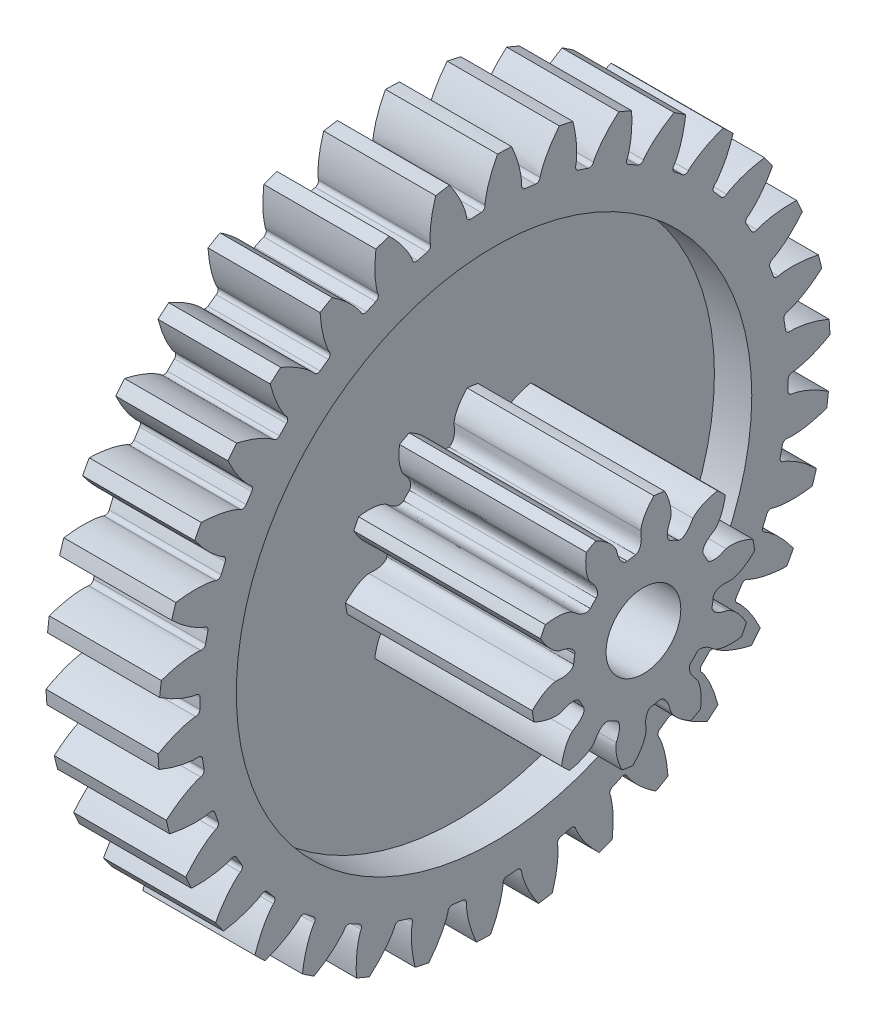
SolidWorks part; units mm, degrees
ref_plane "Plan de face" through (0, 0, 0) normal (0, 0, 1) x (1, 0, 0)
ref_plane "Plan de dessus" through (0, 0, 0) normal (0, 1, 0) x (1, 0, 0)
ref_plane "Plan de droite" through (0, 0, 0) normal (1, 0, 0) x (0, 0, -1)
sketch "Esquisse2" plane through (0, 0, 0) normal (1, 0, 0) x (0, 0, -1)
  arc A0 (8.9927, 0.363) -> (8.9699, 0.736) centre (0, 0) ccw
  arc A1 (8.7729, 2.0092) -> (8.6819, 2.3717) centre (0, 0) ccw
  arc A2 (8.2543, 3.587) -> (8.0983, 3.9266) centre (0, 0) ccw
  arc A3 (7.4547, 5.0426) -> (7.2389, 5.3478) centre (0, 0) ccw
  arc A4 (6.4012, 6.3266) -> (6.133, 6.5869) centre (0, 0) ccw
  arc A5 (5.1297, 7.395) -> (4.8182, 7.6016) centre (0, 0) ccw
  arc A6 (3.6835, 8.2117) -> (3.3394, 8.3575) centre (0, 0) ccw
  arc A7 (2.1119, 8.7487) -> (1.7468, 8.8289) centre (0, 0) ccw
  arc A8 (0.4683, 8.9878) -> (0.0948, 8.9995) centre (0, 0) ccw
  arc A9 (-1.1911, 8.9208) -> (-1.5605, 8.8637) centre (0, 0) ccw
  arc A10 (-2.8101, 8.5501) -> (-3.1626, 8.426) centre (0, 0) ccw
  arc A11 (-4.3333, 7.8881) -> (-4.657, 7.7014) centre (0, 0) ccw
  arc A12 (-5.7089, 6.9576) -> (-5.9929, 6.7146) centre (0, 0) ccw
  arc A13 (-6.8902, 5.7901) -> (-7.1246, 5.499) centre (0, 0) ccw
  arc A14 (-7.8368, 4.4254) -> (-8.0138, 4.0963) centre (0, 0) ccw
  arc A15 (-8.5165, 2.9101) -> (-8.63, 2.554) centre (0, 0) ccw
  arc A16 (-8.9063, 1.2956) -> (-8.9524, 0.9247) centre (0, 0) ccw
  arc A17 (-8.9927, -0.363) -> (-8.9699, -0.736) centre (0, 0) ccw
  arc A18 (-8.7729, -2.0092) -> (-8.6819, -2.3717) centre (0, 0) ccw
  arc A19 (-8.2543, -3.587) -> (-8.0983, -3.9266) centre (0, 0) ccw
  arc A20 (-7.4547, -5.0426) -> (-7.2389, -5.3478) centre (0, 0) ccw
  arc A21 (-6.4012, -6.3266) -> (-6.133, -6.5869) centre (0, 0) ccw
  arc A22 (-5.1297, -7.395) -> (-4.8182, -7.6016) centre (0, 0) ccw
  arc A23 (-3.6835, -8.2117) -> (-3.3394, -8.3575) centre (0, 0) ccw
  arc A24 (-2.1119, -8.7487) -> (-1.7468, -8.8289) centre (0, 0) ccw
  arc A25 (-0.4683, -8.9878) -> (-0.0948, -8.9995) centre (0, 0) ccw
  arc A26 (1.1911, -8.9208) -> (1.5605, -8.8637) centre (0, 0) ccw
  arc A27 (2.8101, -8.5501) -> (3.1626, -8.426) centre (0, 0) ccw
  arc A28 (4.3333, -7.8881) -> (4.657, -7.7014) centre (0, 0) ccw
  arc A29 (5.7089, -6.9576) -> (5.9929, -6.7146) centre (0, 0) ccw
  arc A30 (6.8902, -5.7901) -> (7.1246, -5.499) centre (0, 0) ccw
  arc A31 (7.8368, -4.4254) -> (8.0138, -4.0963) centre (0, 0) ccw
  arc A32 (8.5165, -2.9101) -> (8.63, -2.554) centre (0, 0) ccw
  arc A33 (8.9063, -1.2956) -> (8.9524, -0.9247) centre (0, 0) ccw
  arc A34 (7.987, 0) -> (7.8742, -0.1109) centre (7.9867, -0.1125) ccw
  arc A35 (7.8657, -0.3818) -> (7.9719, -0.4996) centre (7.9781, -0.3873) ccw
  arc A36 (7.8657, -0.3818) -> (7.8742, -0.1109) centre (0, 0) ccw
  arc A37 (7.851, 1.4676) -> (7.7605, 1.3379) centre (7.8714, 1.357) ccw
  arc A38 (7.802, 1.07) -> (7.928, 0.9737) centre (7.9134, 1.0853) ccw
  arc A39 (7.802, 1.07) -> (7.7605, 1.3379) centre (0, 0) ccw
  arc A40 (7.4477, 2.8852) -> (7.3826, 2.7411) centre (7.488, 2.7802) ccw
  arc A41 (7.4725, 2.4854) -> (7.6141, 2.4139) centre (7.5793, 2.5209) ccw
  arc A42 (7.4725, 2.4854) -> (7.3826, 2.7411) centre (0, 0) ccw
  arc A43 (6.7907, 4.2046) -> (6.7532, 4.0509) centre (6.8497, 4.1088) ccw
  arc A44 (6.8886, 3.8161) -> (7.0409, 3.7719) centre (6.987, 3.8706) ccw
  arc A45 (6.8886, 3.8161) -> (6.7532, 4.0509) centre (0, 0) ccw
  arc A46 (5.9025, 5.3808) -> (5.8938, 5.2229) centre (5.978, 5.2975) ccw
  arc A47 (6.0701, 5.0169) -> (6.2279, 5.0014) centre (6.1568, 5.0886) ccw
  arc A48 (6.0701, 5.0169) -> (5.8938, 5.2229) centre (0, 0) ccw
  arc A49 (4.8132, 6.3738) -> (4.8338, 6.2169) centre (4.9028, 6.3057) ccw
  arc A50 (5.0449, 6.0469) -> (5.2029, 6.0607) centre (5.117, 6.1333) ccw
  arc A51 (5.0449, 6.0469) -> (4.8338, 6.2169) centre (0, 0) ccw
  arc A52 (3.5601, 7.1497) -> (3.6091, 6.9993) centre (3.6607, 7.0993) ccw
  arc A53 (3.8479, 6.8709) -> (4.0007, 6.9135) centre (3.9028, 6.9691) ccw
  arc A54 (3.8479, 6.8709) -> (3.6091, 6.9993) centre (0, 0) ccw
  arc A55 (2.1857, 7.6821) -> (2.2616, 7.5433) centre (2.2939, 7.651) ccw
  arc A56 (2.5198, 7.461) -> (2.6622, 7.5309) centre (2.5558, 7.5676) ccw
  arc A57 (2.5198, 7.461) -> (2.2616, 7.5433) centre (0, 0) ccw
  arc A58 (0.7369, 7.9529) -> (0.837, 7.8304) centre (0.8489, 7.9423) ccw
  arc A59 (1.106, 7.797) -> (1.2331, 7.8918) centre (1.1218, 7.9083) ccw
  arc A60 (1.106, 7.797) -> (0.837, 7.8304) centre (0, 0) ccw
  arc A61 (-0.7369, 7.9529) -> (-0.6161, 7.8509) centre (-0.6249, 7.963) ccw
  arc A62 (-0.3455, 7.8674) -> (-0.2381, 7.984) centre (-0.3505, 7.9798) ccw
  arc A63 (-0.3455, 7.8674) -> (-0.6161, 7.8509) centre (0, 0) ccw
  arc A64 (-2.1857, 7.6821) -> (-2.0482, 7.604) centre (-2.0775, 7.7126) ccw
  arc A65 (-1.7853, 7.67) -> (-1.7011, 7.8044) centre (-1.8108, 7.7795) ccw
  arc A66 (-1.7853, 7.67) -> (-2.0482, 7.604) centre (0, 0) ccw
  arc A67 (-3.5601, 7.1497) -> (-3.4106, 7.0981) centre (-3.4593, 7.1996) ccw
  arc A68 (-3.1642, 7.2113) -> (-3.1062, 7.3589) centre (-3.2095, 7.3143) ccw
  arc A69 (-3.1642, 7.2113) -> (-3.4106, 7.0981) centre (0, 0) ccw
  arc A70 (-4.8132, 6.3738) -> (-4.6568, 6.3506) centre (-4.7233, 6.4413) ccw
  arc A71 (-4.4354, 6.5071) -> (-4.4055, 6.6628) centre (-4.4988, 6.6001) ccw
  arc A72 (-4.4354, 6.5071) -> (-4.6568, 6.3506) centre (0, 0) ccw
  arc A73 (-5.9025, 5.3808) -> (-5.7444, 5.3868) centre (-5.8265, 5.4637) ccw
  arc A74 (-5.5556, 5.5813) -> (-5.5547, 5.7399) centre (-5.635, 5.661) ccw
  arc A75 (-5.5556, 5.5813) -> (-5.7444, 5.3868) centre (0, 0) ccw
  arc A76 (-6.7907, 4.2046) -> (-6.6364, 4.2395) centre (-6.7312, 4.3001) ccw
  arc A77 (-6.4866, 4.4654) -> (-6.5149, 4.6215) centre (-6.5792, 4.5292) ccw
  arc A78 (-6.4866, 4.4654) -> (-6.6364, 4.2395) centre (0, 0) ccw
  arc A79 (-7.4477, 2.8852) -> (-7.3024, 2.9479) centre (-7.4067, 2.99) ccw
  arc A80 (-7.1966, 3.1975) -> (-7.2531, 3.3457) centre (-7.2995, 3.2432) ccw
  arc A81 (-7.1966, 3.1975) -> (-7.3024, 2.9479) centre (0, 0) ccw
  arc A82 (-7.851, 1.4676) -> (-7.7198, 1.5559) centre (-7.83, 1.5781) ccw
  arc A83 (-7.6616, 1.8207) -> (-7.7444, 1.956) centre (-7.7711, 1.8467) ccw
  arc A84 (-7.6616, 1.8207) -> (-7.7198, 1.5559) centre (0, 0) ccw
  arc A85 (-7.987, 0) -> (-7.8742, 0.1109) centre (-7.9867, 0.1125) ccw
  arc A86 (-7.8657, 0.3818) -> (-7.9719, 0.4996) centre (-7.9781, 0.3873) ccw
  arc A87 (-7.8657, 0.3818) -> (-7.8742, 0.1109) centre (0, 0) ccw
  arc A88 (-7.851, -1.4676) -> (-7.7605, -1.3379) centre (-7.8714, -1.357) ccw
  arc A89 (-7.802, -1.07) -> (-7.928, -0.9737) centre (-7.9134, -1.0853) ccw
  arc A90 (-7.802, -1.07) -> (-7.7605, -1.3379) centre (0, 0) ccw
  arc A91 (-7.4477, -2.8852) -> (-7.3826, -2.7411) centre (-7.488, -2.7802) ccw
  arc A92 (-7.4725, -2.4854) -> (-7.6141, -2.4139) centre (-7.5793, -2.5209) ccw
  arc A93 (-7.4725, -2.4854) -> (-7.3826, -2.7411) centre (0, 0) ccw
  arc A94 (-6.7907, -4.2046) -> (-6.7532, -4.0509) centre (-6.8497, -4.1088) ccw
  arc A95 (-6.8886, -3.8161) -> (-7.0409, -3.7719) centre (-6.987, -3.8706) ccw
  arc A96 (-6.8886, -3.8161) -> (-6.7532, -4.0509) centre (0, 0) ccw
  arc A97 (-5.9025, -5.3808) -> (-5.8938, -5.2229) centre (-5.978, -5.2975) ccw
  arc A98 (-6.0701, -5.0169) -> (-6.2279, -5.0014) centre (-6.1568, -5.0886) ccw
  arc A99 (-6.0701, -5.0169) -> (-5.8938, -5.2229) centre (0, 0) ccw
  arc A100 (-4.8132, -6.3738) -> (-4.8338, -6.2169) centre (-4.9028, -6.3057) ccw
  arc A101 (-5.0449, -6.0469) -> (-5.2029, -6.0607) centre (-5.117, -6.1333) ccw
  arc A102 (-5.0449, -6.0469) -> (-4.8338, -6.2169) centre (0, 0) ccw
  arc A103 (-3.5601, -7.1497) -> (-3.6091, -6.9993) centre (-3.6607, -7.0993) ccw
  arc A104 (-3.8479, -6.8709) -> (-4.0007, -6.9135) centre (-3.9028, -6.9691) ccw
  arc A105 (-3.8479, -6.8709) -> (-3.6091, -6.9993) centre (0, 0) ccw
  arc A106 (-2.1857, -7.6821) -> (-2.2616, -7.5433) centre (-2.2939, -7.651) ccw
  arc A107 (-2.5198, -7.461) -> (-2.6622, -7.5309) centre (-2.5558, -7.5676) ccw
  arc A108 (-2.5198, -7.461) -> (-2.2616, -7.5433) centre (0, 0) ccw
  arc A109 (-0.7369, -7.9529) -> (-0.837, -7.8304) centre (-0.8489, -7.9423) ccw
  arc A110 (-1.106, -7.797) -> (-1.2331, -7.8918) centre (-1.1218, -7.9083) ccw
  arc A111 (-1.106, -7.797) -> (-0.837, -7.8304) centre (0, 0) ccw
  arc A112 (0.7369, -7.9529) -> (0.6161, -7.8509) centre (0.6249, -7.963) ccw
  arc A113 (0.3455, -7.8674) -> (0.2381, -7.984) centre (0.3505, -7.9798) ccw
  arc A114 (0.3455, -7.8674) -> (0.6161, -7.8509) centre (0, 0) ccw
  arc A115 (2.1857, -7.6821) -> (2.0482, -7.604) centre (2.0775, -7.7126) ccw
  arc A116 (1.7853, -7.67) -> (1.7011, -7.8044) centre (1.8108, -7.7795) ccw
  arc A117 (1.7853, -7.67) -> (2.0482, -7.604) centre (0, 0) ccw
  arc A118 (3.5601, -7.1497) -> (3.4106, -7.0981) centre (3.4593, -7.1996) ccw
  arc A119 (3.1642, -7.2113) -> (3.1062, -7.3589) centre (3.2095, -7.3143) ccw
  arc A120 (3.1642, -7.2113) -> (3.4106, -7.0981) centre (0, 0) ccw
  arc A121 (4.8132, -6.3738) -> (4.6568, -6.3506) centre (4.7233, -6.4413) ccw
  arc A122 (4.4354, -6.5071) -> (4.4055, -6.6628) centre (4.4988, -6.6001) ccw
  arc A123 (4.4354, -6.5071) -> (4.6568, -6.3506) centre (0, 0) ccw
  arc A124 (5.9025, -5.3808) -> (5.7444, -5.3868) centre (5.8265, -5.4637) ccw
  arc A125 (5.5556, -5.5813) -> (5.5547, -5.7399) centre (5.635, -5.661) ccw
  arc A126 (5.5556, -5.5813) -> (5.7444, -5.3868) centre (0, 0) ccw
  arc A127 (6.7907, -4.2046) -> (6.6364, -4.2395) centre (6.7312, -4.3001) ccw
  arc A128 (6.4866, -4.4654) -> (6.5149, -4.6215) centre (6.5792, -4.5292) ccw
  arc A129 (6.4866, -4.4654) -> (6.6364, -4.2395) centre (0, 0) ccw
  arc A130 (7.4477, -2.8852) -> (7.3024, -2.9479) centre (7.4067, -2.99) ccw
  arc A131 (7.1966, -3.1975) -> (7.2531, -3.3457) centre (7.2995, -3.2432) ccw
  arc A132 (7.1966, -3.1975) -> (7.3024, -2.9479) centre (0, 0) ccw
  arc A133 (7.851, -1.4676) -> (7.7198, -1.5559) centre (7.83, -1.5781) ccw
  arc A134 (7.6616, -1.8207) -> (7.7444, -1.956) centre (7.7711, -1.8467) ccw
  arc A135 (7.6616, -1.8207) -> (7.7198, -1.5559) centre (0, 0) ccw
  circle A136 centre (0, 0) radius 1
  spline S0 degree 3 poles (7.987, 0) (8.0286, 0) (8.2037, 0.0282) (8.4818, 0.1115) (8.7713, 0.2415) (8.9323, 0.3284) (8.9927, 0.363) knots 0 0 0 0 0.124841 0.528779 0.867842 1.076016 1.076016 1.076016 1.076016
  spline S1 degree 3 poles (7.928, 0.9737) (7.9687, 0.9787) (8.146, 0.9721) (8.4321, 0.9233) (8.7354, 0.8295) (8.9058, 0.7629) (8.9699, 0.736) knots 0 0 0 0 0.124841 0.528779 0.867842 1.076016 1.076016 1.076016 1.076016
  spline S2 degree 3 poles (7.851, 1.4676) (7.8919, 1.4753) (8.0589, 1.5352) (8.3169, 1.6682) (8.5776, 1.8491) (8.7199, 1.9642) (8.7729, 2.0092) knots 0 0 0 0 0.124841 0.528779 0.867842 1.076016 1.076016 1.076016 1.076016
  spline S3 degree 3 poles (7.6141, 2.4139) (7.6532, 2.4263) (7.8287, 2.4523) (8.1189, 2.4569) (8.4342, 2.4205) (8.6139, 2.3863) (8.6819, 2.3717) knots 0 0 0 0 0.124841 0.528779 0.867842 1.076016 1.076016 1.076016 1.076016
  spline S4 degree 3 poles (7.4477, 2.8852) (7.4865, 2.9003) (7.6396, 2.9898) (7.8687, 3.168) (8.0918, 3.3938) (8.2105, 3.533) (8.2543, 3.587) knots 0 0 0 0 0.124841 0.528779 0.867842 1.076016 1.076016 1.076016 1.076016
  spline S5 degree 3 poles (7.0409, 3.7719) (7.0771, 3.7913) (7.2448, 3.8491) (7.5292, 3.9069) (7.8458, 3.9291) (8.0288, 3.9285) (8.0983, 3.9266) knots 0 0 0 0 0.124841 0.528779 0.867842 1.076016 1.076016 1.076016 1.076016
  spline S6 degree 3 poles (6.7907, 4.2046) (6.8261, 4.2265) (6.9601, 4.3427) (7.1526, 4.5599) (7.3304, 4.8229) (7.4215, 4.9815) (7.4547, 5.0426) knots 0 0 0 0 0.124841 0.528779 0.867842 1.076016 1.076016 1.076016 1.076016
  spline S7 degree 3 poles (6.2279, 5.0014) (6.2599, 5.0271) (6.4141, 5.1148) (6.6831, 5.2239) (6.9903, 5.3039) (7.1702, 5.3369) (7.2389, 5.3478) knots 0 0 0 0 0.124841 0.528779 0.867842 1.076016 1.076016 1.076016 1.076016
  spline S8 degree 3 poles (5.9025, 5.3808) (5.9332, 5.4088) (6.0436, 5.5477) (6.193, 5.7966) (6.3194, 6.0877) (6.3798, 6.2604) (6.4012, 6.3266) knots 0 0 0 0 0.124841 0.528779 0.867842 1.076016 1.076016 1.076016 1.076016
  spline S9 degree 3 poles (5.2029, 6.0607) (5.2296, 6.0918) (5.3651, 6.2063) (5.6094, 6.363) (5.8967, 6.498) (6.0675, 6.5636) (6.133, 6.5869) knots 0 0 0 0 0.124841 0.528779 0.867842 1.076016 1.076016 1.076016 1.076016
  spline S10 degree 3 poles (4.8132, 6.3738) (4.8383, 6.407) (4.9213, 6.5637) (5.0224, 6.8358) (5.0932, 7.1452) (5.1208, 7.3261) (5.1297, 7.395) knots 0 0 0 0 0.124841 0.528779 0.867842 1.076016 1.076016 1.076016 1.076016
  spline S11 degree 3 poles (4.0007, 6.9135) (4.0212, 6.949) (4.1333, 7.0864) (4.3447, 7.2854) (4.6022, 7.4709) (4.7581, 7.5667) (4.8182, 7.6016) knots 0 0 0 0 0.124841 0.528779 0.867842 1.076016 1.076016 1.076016 1.076016
  spline S12 degree 3 poles (3.5601, 7.1497) (3.5787, 7.1869) (3.6315, 7.3563) (3.6808, 7.6423) (3.6935, 7.9594) (3.6875, 8.1423) (3.6835, 8.2117) knots 0 0 0 0 0.124841 0.528779 0.867842 1.076016 1.076016 1.076016 1.076016
  spline S13 degree 3 poles (2.6622, 7.5309) (2.6759, 7.5696) (2.7608, 7.7253) (2.932, 7.9596) (3.1511, 8.1893) (3.2867, 8.3122) (3.3394, 8.3575) knots 0 0 0 0 0.124841 0.528779 0.867842 1.076016 1.076016 1.076016 1.076016
  spline S14 degree 3 poles (2.1857, 7.6821) (2.1971, 7.7221) (2.2179, 7.8983) (2.2139, 8.1885) (2.1681, 8.5026) (2.1286, 8.6812) (2.1119, 8.7487) knots 0 0 0 0 0.124841 0.528779 0.867842 1.076016 1.076016 1.076016 1.076016
  spline S15 degree 3 poles (1.2331, 7.8918) (1.2394, 7.9324) (1.2943, 8.101) (1.4195, 8.3629) (1.5927, 8.6289) (1.7034, 8.7746) (1.7468, 8.8289) knots 0 0 0 0 0.124841 0.528779 0.867842 1.076016 1.076016 1.076016 1.076016
  spline S16 degree 3 poles (0.7369, 7.9529) (0.7408, 7.9944) (0.7288, 8.1713) (0.6715, 8.4559) (0.5688, 8.7562) (0.4971, 8.9245) (0.4683, 8.9878) knots 0 0 0 0 0.124841 0.528779 0.867842 1.076016 1.076016 1.076016 1.076016
  spline S17 degree 3 poles (-0.2381, 7.984) (-0.2393, 8.025) (-0.2163, 8.2009) (-0.1413, 8.4813) (-0.02, 8.7746) (0.0621, 8.9382) (0.0948, 8.9995) knots 0 0 0 0 0.124841 0.528779 0.867842 1.076016 1.076016 1.076016 1.076016
  spline S18 degree 3 poles (-0.7369, 7.9529) (-0.7408, 7.9944) (-0.785, 8.1661) (-0.8937, 8.4353) (-1.0498, 8.7116) (-1.1512, 8.8639) (-1.1911, 8.9208) knots 0 0 0 0 0.124841 0.528779 0.867842 1.076016 1.076016 1.076016 1.076016
  spline S19 degree 3 poles (-1.7011, 7.8044) (-1.7098, 7.8444) (-1.7195, 8.0216) (-1.6973, 8.311) (-1.632, 8.6216) (-1.5814, 8.7974) (-1.5605, 8.8637) knots 0 0 0 0 0.124841 0.528779 0.867842 1.076016 1.076016 1.076016 1.076016
  spline S20 degree 3 poles (-2.1857, 7.6821) (-2.1971, 7.7221) (-2.2722, 7.8828) (-2.4284, 8.1275) (-2.6327, 8.3704) (-2.7603, 8.5015) (-2.8101, 8.5501) knots 0 0 0 0 0.124841 0.528779 0.867842 1.076016 1.076016 1.076016 1.076016
  spline S21 degree 3 poles (-3.1062, 7.3589) (-3.1221, 7.3967) (-3.1642, 7.569) (-3.1956, 7.8576) (-3.1884, 8.1749) (-3.171, 8.357) (-3.1626, 8.426) knots 0 0 0 0 0.124841 0.528779 0.867842 1.076016 1.076016 1.076016 1.076016
  spline S22 degree 3 poles (-3.5601, 7.1497) (-3.5787, 7.1869) (-3.682, 7.3311) (-3.8805, 7.5429) (-4.1259, 7.7441) (-4.2755, 7.8495) (-4.3333, 7.8881) knots 0 0 0 0 0.124841 0.528779 0.867842 1.076016 1.076016 1.076016 1.076016
  spline S23 degree 3 poles (-4.4055, 6.6628) (-4.4281, 6.6971) (-4.5011, 6.8587) (-4.585, 7.1366) (-4.6363, 7.4498) (-4.6526, 7.6321) (-4.657, 7.7014) knots 0 0 0 0 0.124841 0.528779 0.867842 1.076016 1.076016 1.076016 1.076016
  spline S24 degree 3 poles (-4.8132, 6.3738) (-4.8383, 6.407) (-4.9664, 6.5297) (-5.2004, 6.7014) (-5.4787, 6.8541) (-5.645, 6.9302) (-5.7089, 6.9576) knots 0 0 0 0 0.124841 0.528779 0.867842 1.076016 1.076016 1.076016 1.076016
  spline S25 degree 3 poles (-5.5547, 5.7399) (-5.5833, 5.7694) (-5.6848, 5.9148) (-5.8183, 6.1726) (-5.9262, 6.4711) (-5.9757, 6.6472) (-5.9929, 6.7146) knots 0 0 0 0 0.124841 0.528779 0.867842 1.076016 1.076016 1.076016 1.076016
  spline S26 degree 3 poles (-5.9025, 5.3808) (-5.9332, 5.4088) (-6.0816, 5.506) (-6.3432, 5.6317) (-6.6448, 5.7307) (-6.8223, 5.775) (-6.8902, 5.7901) knots 0 0 0 0 0.124841 0.528779 0.867842 1.076016 1.076016 1.076016 1.076016
  spline S27 degree 3 poles (-6.5149, 4.6215) (-6.5483, 4.6452) (-6.6748, 4.7696) (-6.8534, 4.9984) (-7.0144, 5.2719) (-7.0954, 5.436) (-7.1246, 5.499) knots 0 0 0 0 0.124841 0.528779 0.867842 1.076016 1.076016 1.076016 1.076016
  spline S28 degree 3 poles (-6.7907, 4.2046) (-6.8261, 4.2265) (-6.9898, 4.2947) (-7.2701, 4.3703) (-7.5847, 4.4122) (-7.7673, 4.423) (-7.8368, 4.4254) knots 0 0 0 0 0.124841 0.528779 0.867842 1.076016 1.076016 1.076016 1.076016
  spline S29 degree 3 poles (-7.2531, 3.3457) (-7.2904, 3.3629) (-7.4376, 3.4619) (-7.6552, 3.654) (-7.8637, 3.8933) (-7.9735, 4.0396) (-8.0138, 4.0963) knots 0 0 0 0 0.124841 0.528779 0.867842 1.076016 1.076016 1.076016 1.076016
  spline S30 degree 3 poles (-7.4477, 2.8852) (-7.4865, 2.9003) (-7.66, 2.9372) (-7.9493, 2.96) (-8.2663, 2.9434) (-8.4478, 2.9205) (-8.5165, 2.9101) knots 0 0 0 0 0.124841 0.528779 0.867842 1.076016 1.076016 1.076016 1.076016
  spline S31 degree 3 poles (-7.7444, 1.956) (-7.7842, 1.966) (-7.9471, 2.0363) (-8.1962, 2.1851) (-8.4452, 2.3821) (-8.58, 2.5057) (-8.63, 2.554) knots 0 0 0 0 0.124841 0.528779 0.867842 1.076016 1.076016 1.076016 1.076016
  spline S32 degree 3 poles (-7.851, 1.4676) (-7.8919, 1.4753) (-8.0692, 1.4797) (-8.3578, 1.4489) (-8.6664, 1.3743) (-8.8406, 1.3185) (-8.9063, 1.2956) knots 0 0 0 0 0.124841 0.528779 0.867842 1.076016 1.076016 1.076016 1.076016
  spline S33 degree 3 poles (-7.9719, 0.4996) (-8.0129, 0.5022) (-8.1859, 0.5413) (-8.4582, 0.6419) (-8.7391, 0.7897) (-8.8943, 0.8865) (-8.9524, 0.9247) knots 0 0 0 0 0.124841 0.528779 0.867842 1.076016 1.076016 1.076016 1.076016
  spline S34 degree 3 poles (-7.987, 0) (-8.0286, 0) (-8.2037, -0.0282) (-8.4818, -0.1115) (-8.7713, -0.2415) (-8.9323, -0.3284) (-8.9927, -0.363) knots 0 0 0 0 0.124841 0.528779 0.867842 1.076016 1.076016 1.076016 1.076016
  spline S35 degree 3 poles (-7.928, -0.9737) (-7.9687, -0.9787) (-8.146, -0.9721) (-8.4321, -0.9233) (-8.7354, -0.8295) (-8.9058, -0.7629) (-8.9699, -0.736) knots 0 0 0 0 0.124841 0.528779 0.867842 1.076016 1.076016 1.076016 1.076016
  spline S36 degree 3 poles (-7.851, -1.4676) (-7.8919, -1.4753) (-8.0589, -1.5352) (-8.3169, -1.6682) (-8.5776, -1.8491) (-8.7199, -1.9642) (-8.7729, -2.0092) knots 0 0 0 0 0.124841 0.528779 0.867842 1.076016 1.076016 1.076016 1.076016
  spline S37 degree 3 poles (-7.6141, -2.4139) (-7.6532, -2.4263) (-7.8287, -2.4523) (-8.1189, -2.4569) (-8.4342, -2.4205) (-8.6139, -2.3863) (-8.6819, -2.3717) knots 0 0 0 0 0.124841 0.528779 0.867842 1.076016 1.076016 1.076016 1.076016
  spline S38 degree 3 poles (-7.4477, -2.8852) (-7.4865, -2.9003) (-7.6396, -2.9898) (-7.8687, -3.168) (-8.0918, -3.3938) (-8.2105, -3.533) (-8.2543, -3.587) knots 0 0 0 0 0.124841 0.528779 0.867842 1.076016 1.076016 1.076016 1.076016
  spline S39 degree 3 poles (-7.0409, -3.7719) (-7.0771, -3.7913) (-7.2448, -3.8491) (-7.5292, -3.9069) (-7.8458, -3.9291) (-8.0288, -3.9285) (-8.0983, -3.9266) knots 0 0 0 0 0.124841 0.528779 0.867842 1.076016 1.076016 1.076016 1.076016
  spline S40 degree 3 poles (-6.7907, -4.2046) (-6.8261, -4.2265) (-6.9601, -4.3427) (-7.1526, -4.5599) (-7.3304, -4.8229) (-7.4215, -4.9815) (-7.4547, -5.0426) knots 0 0 0 0 0.124841 0.528779 0.867842 1.076016 1.076016 1.076016 1.076016
  spline S41 degree 3 poles (-6.2279, -5.0014) (-6.2599, -5.0271) (-6.4141, -5.1148) (-6.6831, -5.2239) (-6.9903, -5.3039) (-7.1702, -5.3369) (-7.2389, -5.3478) knots 0 0 0 0 0.124841 0.528779 0.867842 1.076016 1.076016 1.076016 1.076016
  spline S42 degree 3 poles (-5.9025, -5.3808) (-5.9332, -5.4088) (-6.0436, -5.5477) (-6.193, -5.7966) (-6.3194, -6.0877) (-6.3798, -6.2604) (-6.4012, -6.3266) knots 0 0 0 0 0.124841 0.528779 0.867842 1.076016 1.076016 1.076016 1.076016
  spline S43 degree 3 poles (-5.2029, -6.0607) (-5.2296, -6.0918) (-5.3651, -6.2063) (-5.6094, -6.363) (-5.8967, -6.498) (-6.0675, -6.5636) (-6.133, -6.5869) knots 0 0 0 0 0.124841 0.528779 0.867842 1.076016 1.076016 1.076016 1.076016
  spline S44 degree 3 poles (-4.8132, -6.3738) (-4.8383, -6.407) (-4.9213, -6.5637) (-5.0224, -6.8358) (-5.0932, -7.1452) (-5.1208, -7.3261) (-5.1297, -7.395) knots 0 0 0 0 0.124841 0.528779 0.867842 1.076016 1.076016 1.076016 1.076016
  spline S45 degree 3 poles (-4.0007, -6.9135) (-4.0212, -6.949) (-4.1333, -7.0864) (-4.3447, -7.2854) (-4.6022, -7.4709) (-4.7581, -7.5667) (-4.8182, -7.6016) knots 0 0 0 0 0.124841 0.528779 0.867842 1.076016 1.076016 1.076016 1.076016
  spline S46 degree 3 poles (-3.5601, -7.1497) (-3.5787, -7.1869) (-3.6315, -7.3563) (-3.6808, -7.6423) (-3.6935, -7.9594) (-3.6875, -8.1423) (-3.6835, -8.2117) knots 0 0 0 0 0.124841 0.528779 0.867842 1.076016 1.076016 1.076016 1.076016
  spline S47 degree 3 poles (-2.6622, -7.5309) (-2.6759, -7.5696) (-2.7608, -7.7253) (-2.932, -7.9596) (-3.1511, -8.1893) (-3.2867, -8.3122) (-3.3394, -8.3575) knots 0 0 0 0 0.124841 0.528779 0.867842 1.076016 1.076016 1.076016 1.076016
  spline S48 degree 3 poles (-2.1857, -7.6821) (-2.1971, -7.7221) (-2.2179, -7.8983) (-2.2139, -8.1885) (-2.1681, -8.5026) (-2.1286, -8.6812) (-2.1119, -8.7487) knots 0 0 0 0 0.124841 0.528779 0.867842 1.076016 1.076016 1.076016 1.076016
  spline S49 degree 3 poles (-1.2331, -7.8918) (-1.2394, -7.9324) (-1.2943, -8.101) (-1.4195, -8.3629) (-1.5927, -8.6289) (-1.7034, -8.7746) (-1.7468, -8.8289) knots 0 0 0 0 0.124841 0.528779 0.867842 1.076016 1.076016 1.076016 1.076016
  spline S50 degree 3 poles (-0.7369, -7.9529) (-0.7408, -7.9944) (-0.7288, -8.1713) (-0.6715, -8.4559) (-0.5688, -8.7562) (-0.4971, -8.9245) (-0.4683, -8.9878) knots 0 0 0 0 0.124841 0.528779 0.867842 1.076016 1.076016 1.076016 1.076016
  spline S51 degree 3 poles (0.2381, -7.984) (0.2393, -8.025) (0.2163, -8.2009) (0.1413, -8.4813) (0.02, -8.7746) (-0.0621, -8.9382) (-0.0948, -8.9995) knots 0 0 0 0 0.124841 0.528779 0.867842 1.076016 1.076016 1.076016 1.076016
  spline S52 degree 3 poles (0.7369, -7.9529) (0.7408, -7.9944) (0.785, -8.1661) (0.8937, -8.4353) (1.0498, -8.7116) (1.1512, -8.8639) (1.1911, -8.9208) knots 0 0 0 0 0.124841 0.528779 0.867842 1.076016 1.076016 1.076016 1.076016
  spline S53 degree 3 poles (1.7011, -7.8044) (1.7098, -7.8444) (1.7195, -8.0216) (1.6973, -8.311) (1.632, -8.6216) (1.5814, -8.7974) (1.5605, -8.8637) knots 0 0 0 0 0.124841 0.528779 0.867842 1.076016 1.076016 1.076016 1.076016
  spline S54 degree 3 poles (2.1857, -7.6821) (2.1971, -7.7221) (2.2722, -7.8828) (2.4284, -8.1275) (2.6327, -8.3704) (2.7603, -8.5015) (2.8101, -8.5501) knots 0 0 0 0 0.124841 0.528779 0.867842 1.076016 1.076016 1.076016 1.076016
  spline S55 degree 3 poles (3.1062, -7.3589) (3.1221, -7.3967) (3.1642, -7.569) (3.1956, -7.8576) (3.1884, -8.1749) (3.171, -8.357) (3.1626, -8.426) knots 0 0 0 0 0.124841 0.528779 0.867842 1.076016 1.076016 1.076016 1.076016
  spline S56 degree 3 poles (3.5601, -7.1497) (3.5787, -7.1869) (3.682, -7.3311) (3.8805, -7.5429) (4.1259, -7.7441) (4.2755, -7.8495) (4.3333, -7.8881) knots 0 0 0 0 0.124841 0.528779 0.867842 1.076016 1.076016 1.076016 1.076016
  spline S57 degree 3 poles (4.4055, -6.6628) (4.4281, -6.6971) (4.5011, -6.8587) (4.585, -7.1366) (4.6363, -7.4498) (4.6526, -7.6321) (4.657, -7.7014) knots 0 0 0 0 0.124841 0.528779 0.867842 1.076016 1.076016 1.076016 1.076016
  spline S58 degree 3 poles (4.8132, -6.3738) (4.8383, -6.407) (4.9664, -6.5297) (5.2004, -6.7014) (5.4787, -6.8541) (5.645, -6.9302) (5.7089, -6.9576) knots 0 0 0 0 0.124841 0.528779 0.867842 1.076016 1.076016 1.076016 1.076016
  spline S59 degree 3 poles (5.5547, -5.7399) (5.5833, -5.7694) (5.6848, -5.9148) (5.8183, -6.1726) (5.9262, -6.4711) (5.9757, -6.6472) (5.9929, -6.7146) knots 0 0 0 0 0.124841 0.528779 0.867842 1.076016 1.076016 1.076016 1.076016
  spline S60 degree 3 poles (5.9025, -5.3808) (5.9332, -5.4088) (6.0816, -5.506) (6.3432, -5.6317) (6.6448, -5.7307) (6.8223, -5.775) (6.8902, -5.7901) knots 0 0 0 0 0.124841 0.528779 0.867842 1.076016 1.076016 1.076016 1.076016
  spline S61 degree 3 poles (6.5149, -4.6215) (6.5483, -4.6452) (6.6748, -4.7696) (6.8534, -4.9984) (7.0144, -5.2719) (7.0954, -5.436) (7.1246, -5.499) knots 0 0 0 0 0.124841 0.528779 0.867842 1.076016 1.076016 1.076016 1.076016
  spline S62 degree 3 poles (6.7907, -4.2046) (6.8261, -4.2265) (6.9898, -4.2947) (7.2701, -4.3703) (7.5847, -4.4122) (7.7673, -4.423) (7.8368, -4.4254) knots 0 0 0 0 0.124841 0.528779 0.867842 1.076016 1.076016 1.076016 1.076016
  spline S63 degree 3 poles (7.2531, -3.3457) (7.2904, -3.3629) (7.4376, -3.4619) (7.6552, -3.654) (7.8637, -3.8933) (7.9735, -4.0396) (8.0138, -4.0963) knots 0 0 0 0 0.124841 0.528779 0.867842 1.076016 1.076016 1.076016 1.076016
  spline S64 degree 3 poles (7.4477, -2.8852) (7.4865, -2.9003) (7.66, -2.9372) (7.9493, -2.96) (8.2663, -2.9434) (8.4478, -2.9205) (8.5165, -2.9101) knots 0 0 0 0 0.124841 0.528779 0.867842 1.076016 1.076016 1.076016 1.076016
  spline S65 degree 3 poles (7.7444, -1.956) (7.7842, -1.966) (7.9471, -2.0363) (8.1962, -2.1851) (8.4452, -2.3821) (8.58, -2.5057) (8.63, -2.554) knots 0 0 0 0 0.124841 0.528779 0.867842 1.076016 1.076016 1.076016 1.076016
  spline S66 degree 3 poles (7.851, -1.4676) (7.8919, -1.4753) (8.0692, -1.4797) (8.3578, -1.4489) (8.6664, -1.3743) (8.8406, -1.3185) (8.9063, -1.2956) knots 0 0 0 0 0.124841 0.528779 0.867842 1.076016 1.076016 1.076016 1.076016
  spline S67 degree 3 poles (7.9719, -0.4996) (8.0129, -0.5022) (8.1859, -0.5413) (8.4582, -0.6419) (8.7391, -0.7897) (8.8943, -0.8865) (8.9524, -0.9247) knots 0 0 0 0 0.124841 0.528779 0.867842 1.076016 1.076016 1.076016 1.076016
  dimension "D1" = 2
extrude "Boss.-Extru.1" add sketch "Esquisse2" along normal blind 3
sketch "Esquisse3" plane through (3, 0, 0) normal (1, 0, 0) x (0, 0, -1)
  circle A0 centre (0, 0) radius 6.9
  dimension "D1" = 13.8
extrude "Enlèv. mat.-Extru.1" cut sketch "Esquisse3" against normal blind 1
sketch "Esquisse4" plane through (2, 0, 0) normal (1, 0, 0) x (0, 0, -1)
  arc A0 (2.9773, 0.3683) -> (2.9271, 0.6573) centre (0, 0) ccw
  arc A1 (2.1922, 2.048) -> (1.9817, 2.2523) centre (0, 0) ccw
  arc A2 (0.5698, 2.9454) -> (0.2794, 2.987) centre (0, 0) ccw
  arc A3 (-1.2703, 2.7178) -> (-1.5297, 2.5807) centre (0, 0) ccw
  arc A4 (-2.6252, 1.4521) -> (-2.7544, 1.1887) centre (0, 0) ccw
  arc A5 (-2.9773, -0.3683) -> (-2.9271, -0.6573) centre (0, 0) ccw
  arc A6 (-2.1922, -2.048) -> (-1.9817, -2.2523) centre (0, 0) ccw
  arc A7 (-0.5698, -2.9454) -> (-0.2794, -2.987) centre (0, 0) ccw
  arc A8 (1.2703, -2.7178) -> (1.5297, -2.5807) centre (0, 0) ccw
  arc A9 (2.6252, -1.4521) -> (2.7544, -1.1887) centre (0, 0) ccw
  arc A10 (1.8368, -0.3764) -> (1.8687, -0.154) centre (0, 0) ccw
  arc A11 (1.7073, 0.7751) -> (1.6023, 0.9738) centre (0, 0) ccw
  arc A12 (0.9256, 1.6306) -> (0.7239, 1.7296) centre (0, 0) ccw
  arc A13 (-0.2096, 1.8632) -> (-0.431, 1.8248) centre (0, 0) ccw
  arc A14 (-1.2648, 1.3842) -> (-1.4213, 1.2229) centre (0, 0) ccw
  arc A15 (-1.8368, 0.3764) -> (-1.8687, 0.154) centre (0, 0) ccw
  arc A16 (-1.7073, -0.7751) -> (-1.6023, -0.9738) centre (0, 0) ccw
  arc A17 (-0.9256, -1.6306) -> (-0.7239, -1.7296) centre (0, 0) ccw
  arc A18 (0.2096, -1.8632) -> (0.431, -1.8248) centre (0, 0) ccw
  arc A19 (1.2648, -1.3842) -> (1.4213, -1.2229) centre (0, 0) ccw
  circle A20 centre (0, 0) radius 1
  spline S0 degree 3 poles (2.349, 0) (2.3611, 0) (2.4126, 0.0085) (2.4945, 0.0326) (2.6584, 0.1065) (2.823, 0.2207) (2.9394, 0.3292) (2.9773, 0.3683) knots 0 0 0 0 0.036251 0.155621 0.255291 0.575255 0.744085 0.744085 0.744085 0.744085
  spline S1 degree 3 poles (2.2114, 0.7921) (2.2228, 0.7962) (2.2741, 0.8056) (2.3594, 0.8105) (2.5386, 0.7962) (2.7321, 0.7442) (2.8782, 0.6813) (2.9271, 0.6573) knots 0 0 0 0 0.036251 0.155621 0.255291 0.575255 0.744085 0.744085 0.744085 0.744085
  spline S2 degree 3 poles (1.9004, 1.3807) (1.9102, 1.3878) (1.9469, 1.4249) (1.9989, 1.4926) (2.0881, 1.6487) (2.1541, 1.8379) (2.1845, 1.9941) (2.1922, 2.048) knots 0 0 0 0 0.036251 0.155621 0.255291 0.575255 0.744085 0.744085 0.744085 0.744085
  spline S3 degree 3 poles (1.3235, 1.9407) (1.3303, 1.9507) (1.3663, 1.9885) (1.4324, 2.0425) (1.5858, 2.1363) (1.7728, 2.2079) (1.9281, 2.243) (1.9817, 2.2523) knots 0 0 0 0 0.036251 0.155621 0.255291 0.575255 0.744085 0.744085 0.744085 0.744085
  spline S4 degree 3 poles (0.7259, 2.234) (0.7296, 2.2455) (0.7375, 2.2971) (0.7398, 2.3825) (0.7202, 2.5612) (0.6625, 2.753) (0.5952, 2.8973) (0.5698, 2.9454) knots 0 0 0 0 0.036251 0.155621 0.255291 0.575255 0.744085 0.744085 0.744085 0.744085
  spline S5 degree 3 poles (-0.07, 2.348) (-0.0704, 2.36) (-0.0634, 2.4118) (-0.0417, 2.4943) (0.0272, 2.6604) (0.1365, 2.8283) (0.2415, 2.9479) (0.2794, 2.987) knots 0 0 0 0 0.036251 0.155621 0.255291 0.575255 0.744085 0.744085 0.744085 0.744085
  spline S6 degree 3 poles (-0.7259, 2.234) (-0.7296, 2.2455) (-0.7536, 2.2919) (-0.8019, 2.3623) (-0.9228, 2.4954) (-1.0823, 2.6166) (-1.2215, 2.6938) (-1.2703, 2.7178) knots 0 0 0 0 0.036251 0.155621 0.255291 0.575255 0.744085 0.744085 0.744085 0.744085
  spline S7 degree 3 poles (-1.4367, 1.8584) (-1.4441, 1.8679) (-1.4689, 1.9139) (-1.4999, 1.9934) (-1.5417, 2.1683) (-1.552, 2.3684) (-1.5374, 2.5268) (-1.5297, 2.5807) knots 0 0 0 0 0.036251 0.155621 0.255291 0.575255 0.744085 0.744085 0.744085 0.744085
  spline S8 degree 3 poles (-1.9004, 1.3807) (-1.9102, 1.3878) (-1.9568, 1.4112) (-2.0373, 1.4398) (-2.2133, 1.4764) (-2.4136, 1.4808) (-2.5715, 1.4614) (-2.6252, 1.4521) knots 0 0 0 0 0.036251 0.155621 0.255291 0.575255 0.744085 0.744085 0.744085 0.744085
  spline S9 degree 3 poles (-2.2547, 0.659) (-2.2663, 0.6624) (-2.3133, 0.6849) (-2.3852, 0.7311) (-2.5218, 0.848) (-2.6477, 1.0038) (-2.729, 1.1406) (-2.7544, 1.1887) knots 0 0 0 0 0.036251 0.155621 0.255291 0.575255 0.744085 0.744085 0.744085 0.744085
  spline S10 degree 3 poles (-2.349, 0) (-2.3611, 0) (-2.4126, -0.0085) (-2.4945, -0.0326) (-2.6584, -0.1065) (-2.823, -0.2207) (-2.9394, -0.3292) (-2.9773, -0.3683) knots 0 0 0 0 0.036251 0.155621 0.255291 0.575255 0.744085 0.744085 0.744085 0.744085
  spline S11 degree 3 poles (-2.2114, -0.7921) (-2.2228, -0.7962) (-2.2741, -0.8056) (-2.3594, -0.8105) (-2.5386, -0.7962) (-2.7321, -0.7442) (-2.8782, -0.6813) (-2.9271, -0.6573) knots 0 0 0 0 0.036251 0.155621 0.255291 0.575255 0.744085 0.744085 0.744085 0.744085
  spline S12 degree 3 poles (-1.9004, -1.3807) (-1.9102, -1.3878) (-1.9469, -1.4249) (-1.9989, -1.4926) (-2.0881, -1.6487) (-2.1541, -1.8379) (-2.1845, -1.9941) (-2.1922, -2.048) knots 0 0 0 0 0.036251 0.155621 0.255291 0.575255 0.744085 0.744085 0.744085 0.744085
  spline S13 degree 3 poles (-1.3235, -1.9407) (-1.3303, -1.9507) (-1.3663, -1.9885) (-1.4324, -2.0425) (-1.5858, -2.1363) (-1.7728, -2.2079) (-1.9281, -2.243) (-1.9817, -2.2523) knots 0 0 0 0 0.036251 0.155621 0.255291 0.575255 0.744085 0.744085 0.744085 0.744085
  spline S14 degree 3 poles (-0.7259, -2.234) (-0.7296, -2.2455) (-0.7375, -2.2971) (-0.7398, -2.3825) (-0.7202, -2.5612) (-0.6625, -2.753) (-0.5952, -2.8973) (-0.5698, -2.9454) knots 0 0 0 0 0.036251 0.155621 0.255291 0.575255 0.744085 0.744085 0.744085 0.744085
  spline S15 degree 3 poles (0.07, -2.348) (0.0704, -2.36) (0.0634, -2.4118) (0.0417, -2.4943) (-0.0272, -2.6604) (-0.1365, -2.8283) (-0.2415, -2.9479) (-0.2794, -2.987) knots 0 0 0 0 0.036251 0.155621 0.255291 0.575255 0.744085 0.744085 0.744085 0.744085
  spline S16 degree 3 poles (0.7259, -2.234) (0.7296, -2.2455) (0.7536, -2.2919) (0.8019, -2.3623) (0.9228, -2.4954) (1.0823, -2.6166) (1.2215, -2.6938) (1.2703, -2.7178) knots 0 0 0 0 0.036251 0.155621 0.255291 0.575255 0.744085 0.744085 0.744085 0.744085
  spline S17 degree 3 poles (1.4367, -1.8584) (1.4441, -1.8679) (1.4689, -1.9139) (1.4999, -1.9934) (1.5417, -2.1683) (1.552, -2.3684) (1.5374, -2.5268) (1.5297, -2.5807) knots 0 0 0 0 0.036251 0.155621 0.255291 0.575255 0.744085 0.744085 0.744085 0.744085
  spline S18 degree 3 poles (1.9004, -1.3807) (1.9102, -1.3878) (1.9568, -1.4112) (2.0373, -1.4398) (2.2133, -1.4764) (2.4136, -1.4808) (2.5715, -1.4614) (2.6252, -1.4521) knots 0 0 0 0 0.036251 0.155621 0.255291 0.575255 0.744085 0.744085 0.744085 0.744085
  spline S19 degree 3 poles (2.2547, -0.659) (2.2663, -0.6624) (2.3133, -0.6849) (2.3852, -0.7311) (2.5218, -0.848) (2.6477, -1.0038) (2.729, -1.1406) (2.7544, -1.1887) knots 0 0 0 0 0.036251 0.155621 0.255291 0.575255 0.744085 0.744085 0.744085 0.744085
  spline S20 degree 3 poles (2.349, 0) (2.2648, 0) (2.1034, 0.0291) (1.8817, -0.0633) (1.8687, -0.154) knots 0 0 0 0 0.252618 0.527509 0.527509 0.527509 0.527509
  spline S21 degree 3 poles (2.2547, -0.659) (2.1739, -0.6353) (2.0108, -0.618) (1.8238, -0.4671) (1.8368, -0.3764) knots 0 0 0 0 0.252618 0.527509 0.527509 0.527509 0.527509
  spline S22 degree 3 poles (1.9004, 1.3807) (1.8323, 1.3312) (1.6846, 1.2599) (1.5595, 1.0548) (1.6023, 0.9738) knots 0 0 0 0 0.252618 0.527509 0.527509 0.527509 0.527509
  spline S23 degree 3 poles (2.2114, 0.7921) (2.1321, 0.7637) (1.99, 0.682) (1.7501, 0.6941) (1.7073, 0.7751) knots 0 0 0 0 0.252618 0.527509 0.527509 0.527509 0.527509
  spline S24 degree 3 poles (0.7259, 2.234) (0.6999, 2.1539) (0.6223, 2.0095) (0.6416, 1.77) (0.7239, 1.7296) knots 0 0 0 0 0.252618 0.527509 0.527509 0.527509 0.527509
  spline S25 degree 3 poles (1.3235, 1.9407) (1.276, 1.8711) (1.2091, 1.7214) (1.0079, 1.5902) (0.9256, 1.6306) knots 0 0 0 0 0.252618 0.527509 0.527509 0.527509 0.527509
  spline S26 degree 3 poles (-0.7259, 2.234) (-0.6999, 2.1539) (-0.6776, 1.9915) (-0.5213, 1.8091) (-0.431, 1.8248) knots 0 0 0 0 0.252618 0.527509 0.527509 0.527509 0.527509
  spline S27 degree 3 poles (-0.07, 2.348) (-0.0675, 2.2638) (-0.0336, 2.1034) (-0.1193, 1.8789) (-0.2096, 1.8632) knots 0 0 0 0 0.252618 0.527509 0.527509 0.527509 0.527509
  spline S28 degree 3 poles (-1.9004, 1.3807) (-1.8323, 1.3312) (-1.7188, 1.2128) (-1.4851, 1.1572) (-1.4213, 1.2229) knots 0 0 0 0 0.252618 0.527509 0.527509 0.527509 0.527509
  spline S29 degree 3 poles (-1.4367, 1.8584) (-1.3852, 1.7918) (-1.2635, 1.6819) (-1.2009, 1.4499) (-1.2648, 1.3842) knots 0 0 0 0 0.252618 0.527509 0.527509 0.527509 0.527509
  spline S30 degree 3 poles (-2.349, 0) (-2.2648, 0) (-2.1034, -0.0291) (-1.8817, 0.0633) (-1.8687, 0.154) knots 0 0 0 0 0.252618 0.527509 0.527509 0.527509 0.527509
  spline S31 degree 3 poles (-2.2547, 0.659) (-2.1739, 0.6353) (-2.0108, 0.618) (-1.8238, 0.4671) (-1.8368, 0.3764) knots 0 0 0 0 0.252618 0.527509 0.527509 0.527509 0.527509
  spline S32 degree 3 poles (-1.9004, -1.3807) (-1.8323, -1.3312) (-1.6846, -1.2599) (-1.5595, -1.0548) (-1.6023, -0.9738) knots 0 0 0 0 0.252618 0.527509 0.527509 0.527509 0.527509
  spline S33 degree 3 poles (-2.2114, -0.7921) (-2.1321, -0.7637) (-1.99, -0.682) (-1.7501, -0.6941) (-1.7073, -0.7751) knots 0 0 0 0 0.252618 0.527509 0.527509 0.527509 0.527509
  spline S34 degree 3 poles (-0.7259, -2.234) (-0.6999, -2.1539) (-0.6223, -2.0095) (-0.6416, -1.77) (-0.7239, -1.7296) knots 0 0 0 0 0.252618 0.527509 0.527509 0.527509 0.527509
  spline S35 degree 3 poles (-1.3235, -1.9407) (-1.276, -1.8711) (-1.2091, -1.7214) (-1.0079, -1.5902) (-0.9256, -1.6306) knots 0 0 0 0 0.252618 0.527509 0.527509 0.527509 0.527509
  spline S36 degree 3 poles (0.7259, -2.234) (0.6999, -2.1539) (0.6776, -1.9915) (0.5213, -1.8091) (0.431, -1.8248) knots 0 0 0 0 0.252618 0.527509 0.527509 0.527509 0.527509
  spline S37 degree 3 poles (0.07, -2.348) (0.0675, -2.2638) (0.0336, -2.1034) (0.1193, -1.8789) (0.2096, -1.8632) knots 0 0 0 0 0.252618 0.527509 0.527509 0.527509 0.527509
  spline S38 degree 3 poles (1.9004, -1.3807) (1.8323, -1.3312) (1.7188, -1.2128) (1.4851, -1.1572) (1.4213, -1.2229) knots 0 0 0 0 0.252618 0.527509 0.527509 0.527509 0.527509
  spline S39 degree 3 poles (1.4367, -1.8584) (1.3852, -1.7918) (1.2635, -1.6819) (1.2009, -1.4499) (1.2648, -1.3842) knots 0 0 0 0 0.252618 0.527509 0.527509 0.527509 0.527509
extrude "Boss.-Extru.2" add sketch "Esquisse4" along normal blind 5
